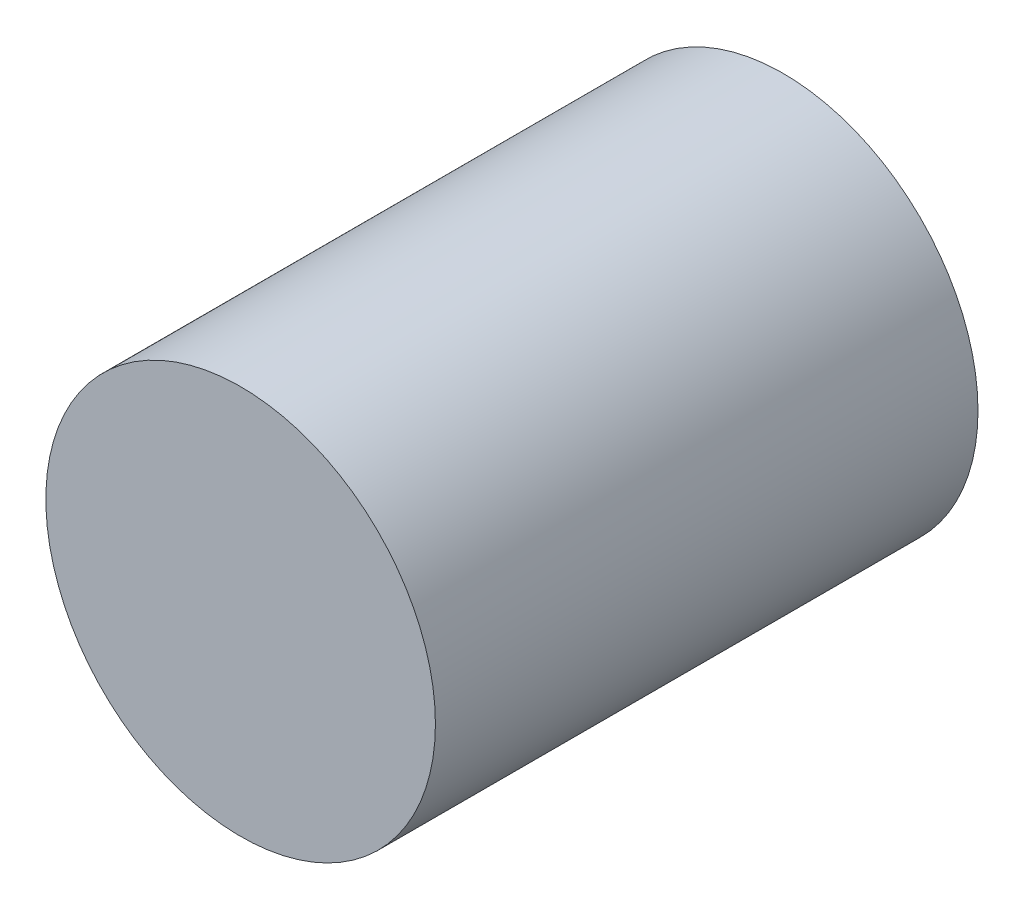
SolidWorks part; units mm, degrees
material "AISI Type A2 Tool Steel"
ref_plane "Front Plane" through (0, 0, 0) normal (0, 0, 1) x (1, 0, 0)
ref_plane "Top Plane" through (0, 0, 0) normal (0, 1, 0) x (1, 0, 0)
ref_plane "Right Plane" through (0, 0, 0) normal (1, 0, 0) x (0, 0, -1)
sketch "Sketch2" plane through (0, 0, 0) normal (0, 0, 1) x (1, 0, 0)
  circle A0 centre (0, 0) radius 7.18
  dimension "D1" = 14.36
extrude "Boss-Extrude1" add sketch "Sketch2" along normal blind 20
